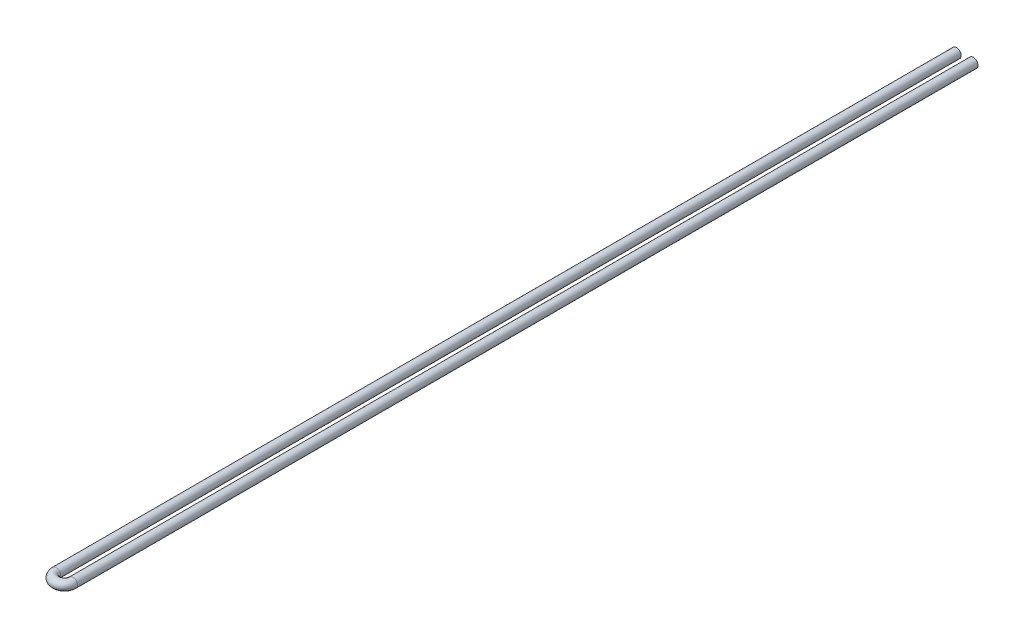
SolidWorks part; units mm, degrees
ref_plane "Front Plane" through (0, 0, 0) normal (0, 0, 1) x (1, 0, 0)
ref_plane "Top Plane" through (0, 0, 0) normal (0, 1, 0) x (1, 0, 0)
ref_plane "Right Plane" through (0, 0, 0) normal (1, 0, 0) x (0, 0, -1)
sketch "Sketch1" plane through (0, 0, 0) normal (0, 1, 0) x (1, 0, 0)
  line L0 (0, -300) -> (0, -2440)
  line L2 (-40, -300) -> (-40, -2440)
  arc A0 (-40, -2440) -> (0, -2440) centre (-20, -2440) ccw
  dimension "D1" = 2140
  dimension "D2" = 40
ref_plane "Plane1" through (0, 0, 300) normal (0, 0, -1) x (-1, 0, 0)
sketch "Sketch2" plane through (0, 0, 300) normal (0, 0, -1) x (-1, 0, 0)
  circle A0 centre (0, 0) radius 9.95
  circle A1 centre (0, 0) radius 11.1
  dimension "D1" = 22.2
  dimension "D2" = 19.9
sweep "Sweep1" add profiles "Sketch2" path "Sketch1"
